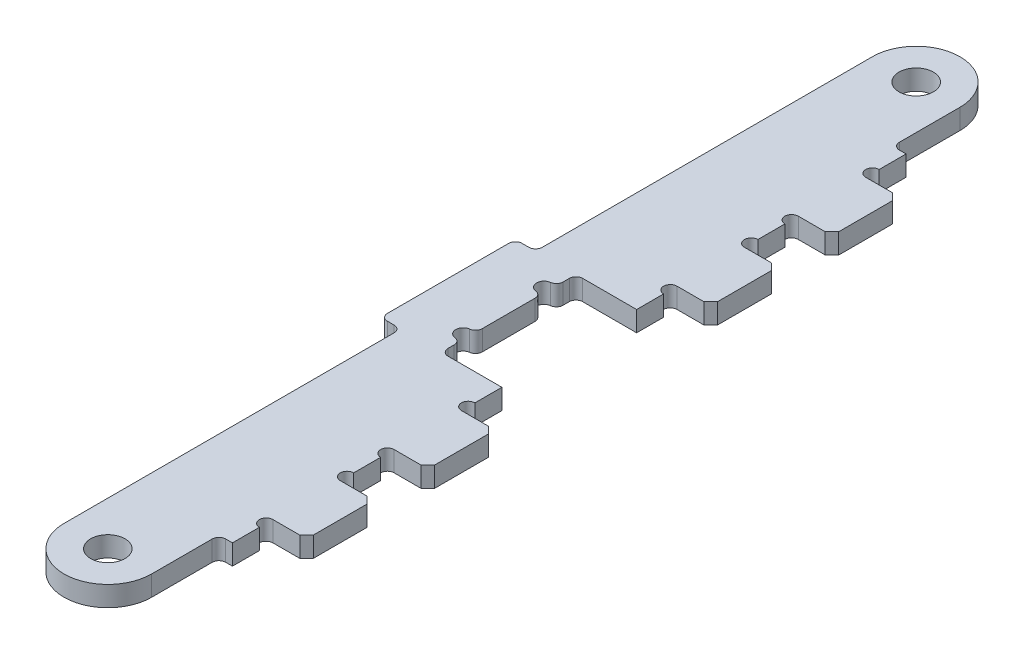
SolidWorks part; units mm, degrees
material "碳板"
ref_plane "前视基准面" through (0, 0, 0) normal (0, 0, 1) x (1, 0, 0)
ref_plane "上视基准面" through (0, 0, 0) normal (0, 1, 0) x (1, 0, 0)
ref_plane "右视基准面" through (0, 0, 0) normal (1, 0, 0) x (0, 0, -1)
sketch "草图1" plane through (0, 0, 0) normal (0, 1, 0) x (1, 0, 0)
  line L0 (0, 61.3094) -> (0, -53.1134) construction
  line L1 (-68.3001, 0) -> (75.8533, 0) construction
  line L2 (-6.5, 60) -> (-6.5, -60)
  line L3 (6.5, 60) -> (6.5, 50)
  line L4 (8.5, -50) -> (8.5, -44)
  line L5 (6.5, 50) -> (8.5, 50)
  line L6 (6.5, -60) -> (6.5, -50)
  line L7 (6.5, -50) -> (8.5, -50)
  line L8 (8.5, 10) -> (-0.5, 10)
  line L9 (-0.5, 10) -> (-0.5, -10)
  line L10 (-6.5, 10) -> (-9.5, 10)
  line L11 (-9.5, 10) -> (-9.5, -10)
  line L12 (-9.5, -10) -> (-6.5, -10)
  line L13 (8.5, -10) -> (-0.5, -10)
  line L14 (8.5, 44) -> (13.5, 44)
  line L15 (13.5, 44) -> (13.5, 34)
  line L16 (13.5, 34) -> (8.5, 34)
  line L17 (8.5, 26) -> (13.5, 26)
  line L18 (13.5, 26) -> (13.5, 16)
  line L19 (13.5, 16) -> (8.5, 16)
  line L20 (8.5, 44) -> (8.5, 50)
  line L21 (8.5, 26) -> (8.5, 34)
  line L22 (8.5, -44) -> (13.5, -44)
  line L23 (13.5, -44) -> (13.5, -34)
  line L24 (13.5, -34) -> (8.5, -34)
  line L25 (8.5, -26) -> (13.5, -26)
  line L26 (13.5, -26) -> (13.5, -16)
  line L27 (13.5, -16) -> (8.5, -16)
  line L28 (8.5, -16) -> (8.5, 16)
  line L29 (8.5, -34) -> (8.5, -26)
  circle A0 centre (0, 60) radius 2.55
  circle A1 centre (0, 60) radius 6.5
  circle A2 centre (0, -60) radius 2.55
  circle A3 centre (0, -60) radius 6.5
  arc A4 (8.5, 46) -> (8.5, 44) centre (8.5, 45) ccw
  arc A5 (8.5, 34) -> (8.5, 32) centre (8.5, 33) ccw
  arc A6 (8.5, 28) -> (8.5, 26) centre (8.5, 27) ccw
  arc A7 (8.5, 16) -> (8.5, 14) centre (8.5, 15) ccw
  arc A8 (8.5, -46) -> (8.5, -44) centre (8.5, -45) cw
  arc A9 (8.5, -34) -> (8.5, -32) centre (8.5, -33) cw
  arc A10 (8.5, -28) -> (8.5, -26) centre (8.5, -27) cw
  arc A11 (8.5, -16) -> (8.5, -14) centre (8.5, -15) cw
  point P27 (-3.5, 0)
  point P29 (-0.5, 0)
  dimension "D1" = 5.1
  dimension "D2" = 13
  dimension "D10" = 2
  dimension "D11" = 2
  dimension "D3" = 60
  dimension "D4" = 8.5
  dimension "D5" = 100
  dimension "D6" = 20
  dimension "D7" = 9
  dimension "D8" = 3
  dimension "D12" = 6
  dimension "D13" = 10
  dimension "D14" = 5
  dimension "D15" = 8
extrude "凸台-拉伸1" add sketch "草图1" along normal blind 3
fillet "圆角1" radius 1 8 edges at (6.5, 1.5, -50) (-0.5, 1.5, -10) (-0.5, 1.5, 10) (6.5, 1.5, 50) (-6.5, 1.5, 10) (-9.5, 1.5, 10) (-9.5, 1.5, -10) (-6.5, 1.5, -10)
chamfer "倒角1" distance 1 angle 45 8 edges at (13.5, 1.5, 44) (13.5, 1.5, 34) (13.5, 1.5, 26) (13.5, 1.5, 16) (13.5, 1.5, -16) (13.5, 1.5, -26) (13.5, 1.5, -34) (13.5, 1.5, -44)
sketch "草图2" plane through (0, 3, 0) normal (0, 1, 0) x (1, 0, 0)
  line L0 (8.5, 14) -> (8.5, -14) construction
  line L1 (-21.3911, 0) -> (25.9861, 0) construction
  circle A0 centre (6.75, 6) radius 1.1
  circle A1 centre (-1.25, 6) radius 1.1
  circle A2 centre (6.75, -6) radius 1.1
  circle A3 centre (-1.25, -6) radius 1.1
  point P15 (0, 0)
  dimension "D1" = 2.2
  dimension "D3" = 8
  dimension "D2" = 1.75
  dimension "D4" = 12
extrude "切除-拉伸1" cut sketch "草图2" against normal through all
fillet "圆角2" radius 1 4 edges at (-0.5, 1.5, 5.1953) (-0.5, 1.5, 6.8047) (-0.5, 1.5, -6.8047) (-0.5, 1.5, -5.1953)
